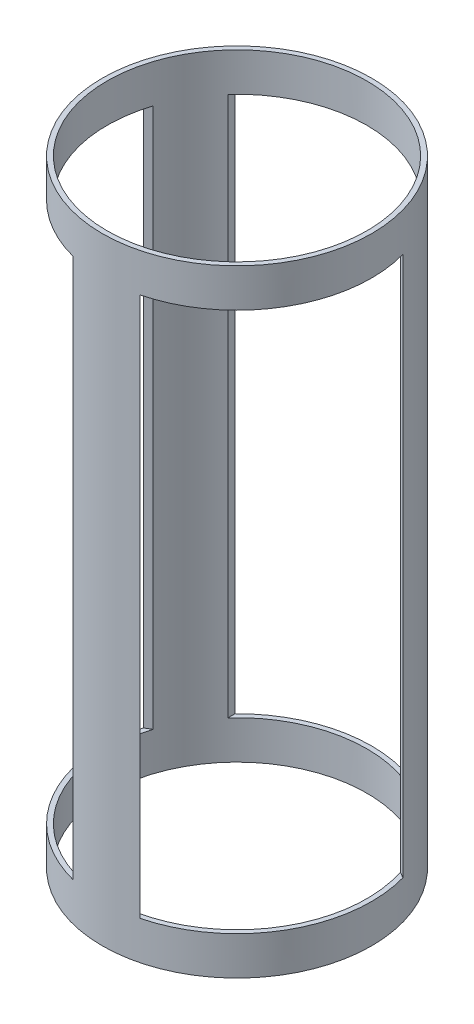
SolidWorks part; units mm, degrees
material "6061-T6 (SS)"
ref_plane "Front Plane" through (0, 0, 0) normal (0, 0, 1) x (1, 0, 0)
ref_plane "Top Plane" through (0, 0, 0) normal (0, 1, 0) x (1, 0, 0)
ref_plane "Right Plane" through (0, 0, 0) normal (1, 0, 0) x (0, 0, -1)
sketch "Sketch1" plane through (0, 0, 0) normal (0, 1, 0) x (1, 0, 0)
  circle A0 centre (0, 0) radius 88.9
  circle A1 centre (0, 0) radius 85.725
  dimension "D1" = 177.8
  dimension "D2" = 171.45
extrude "Boss-Extrude1" add sketch "Sketch1" along normal mid plane 407.162
sketch "Sketch2" plane through (0, 0, 0) normal (0, 0, 1) x (1, 0, 0)
  line L0 (85.725, 203.581) -> (-85.725, 203.581) construction
  line L1 (-63.5, -178.181) -> (63.5, -178.181)
  line L2 (-63.5, -178.181) -> (-63.5, 178.181)
  line L3 (-63.5, 178.181) -> (63.5, 178.181)
  line L4 (63.5, -178.181) -> (63.5, 178.181)
  line L5 (-63.5, -178.181) -> (63.5, 178.181) construction
  line L6 (-63.5, 178.181) -> (63.5, -178.181) construction
  line L7 (88.9, -203.581) -> (88.9, 203.581) construction
  point P0 (0, 0)
  dimension "D1" = 25.4
  dimension "D2" = 25.4
extrude "Cut-Extrude1" cut sketch "Sketch2" against normal up to surface (62.217 mm away)
pattern_circular "CirPattern1" count 3 over 360 about axis through (0, 0, 0) along (0, 1, 0) of "Cut-Extrude1"
ref_plane "Plane1" through (88.9, 0, 0) normal (1, 0, 0) x (0, 0, -1)
sketch "Sketch4" plane through (88.9, 0, 0) normal (1, 0, 0) x (0, 0, -1)
  line L0 (0, 97.79) -> (0, -97.79) construction
  line L1 (88.9, 203.581) -> (-88.9, 203.581) construction
  circle A0 centre (0, 197.231) radius 1.4351
  dimension "D1" = 2.8702
  dimension "D2" = 6.35
extrude "Cut-Extrude3" [suppressed] cut sketch "Sketch4" against normal blind 15.24
pattern_circular "CirPattern3" [suppressed] count 12 over 360
mirror "Mirror1" [suppressed] about plane through (0, 0, 0) normal (0, 1, 0)
ref_plane "Plane2" [suppressed] through (0, 0, 88.9) normal (0, 0, 1) x (1, 0, 0)
sketch "Sketch5" [suppressed] plane through (0, 0, 88.9) normal (0, 0, 1) x (1, 0, 0)
  circle A0 centre (0, -65.7606) radius 1.4351
  circle A1 centre (0, 65.7606) radius 1.4351
  circle A2 centre (0, 197.231) radius 1.4351 construction
  circle A3 centre (0, -197.231) radius 1.4351 construction
  dimension "D1" = 131.4704
  dimension "D2" = 131.4704
  dimension "D3" = 2.8702
  dimension "D4" = 2.8702
extrude "Cut-Extrude4" [suppressed] cut sketch "Sketch5" against normal blind 46.482
pattern_circular "CirPattern4" [suppressed] count 3 over 360
